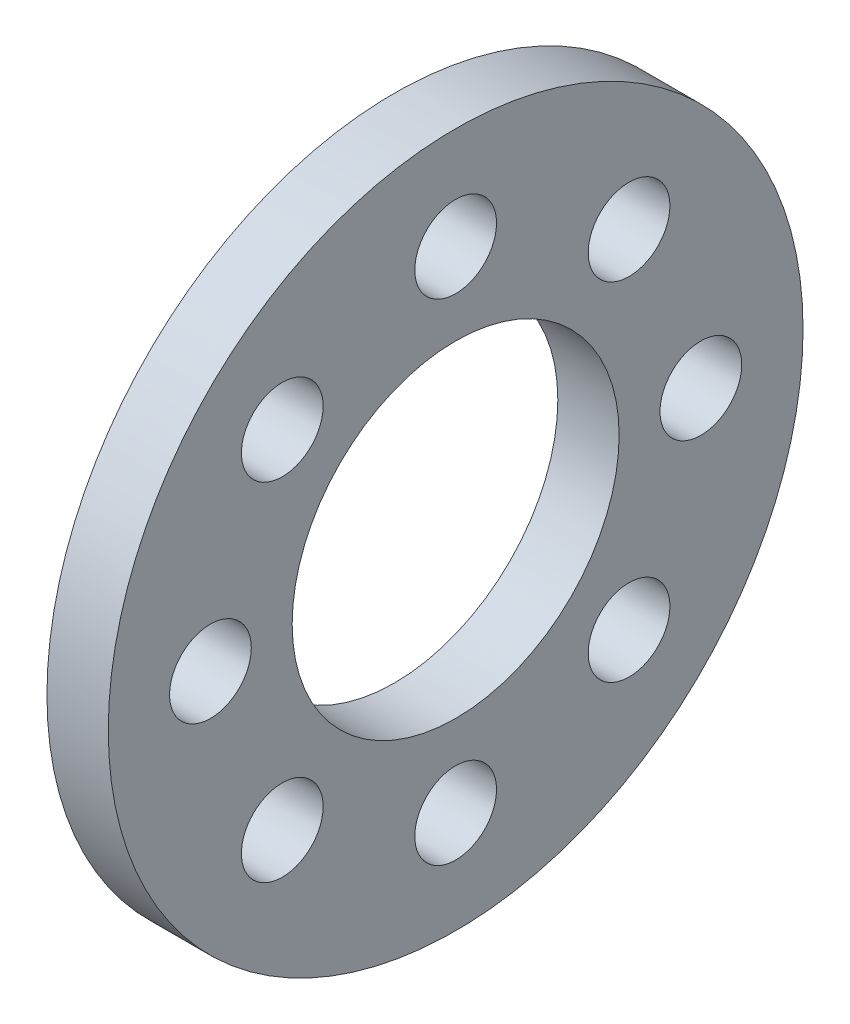
SolidWorks part; units mm, degrees
ref_plane "Front Plane" through (0, 0, 0) normal (0, 0, 1) x (1, 0, 0)
ref_plane "Top Plane" through (0, 0, 0) normal (0, 1, 0) x (1, 0, 0)
ref_plane "Right Plane" through (0, 0, 0) normal (1, 0, 0) x (0, 0, -1)
sketch "Sketch1" plane through (0, 0, 0) normal (1, 0, 0) x (0, 0, -1)
  line L0 (0, 0) -> (0, 12) construction
  circle A0 centre (0, 0) radius 17
  circle A1 centre (0, 12) radius 2
  circle A2 centre (8.4853, 8.4853) radius 2
  circle A3 centre (12, 0) radius 2
  circle A4 centre (8.4853, -8.4853) radius 2
  circle A5 centre (0, -12) radius 2
  circle A6 centre (-8.4853, -8.4853) radius 2
  circle A7 centre (-12, 0) radius 2
  circle A8 centre (-8.4853, 8.4853) radius 2
  circle A9 centre (0, 0) radius 8
  point P21 (0, 0)
  dimension "D1" = 34
  dimension "D3" = 4
  dimension "D5" = 16
  dimension "D2" = 12
  dimension "D4" = 8
extrude "Boss-Extrude1" add sketch "Sketch1" along normal blind 3
sketch "Sketch2" plane through (0, 0, 0) normal (-1, 0, 0) x (0, 0, 1)
  line L0 (0, 0) -> (-4.8186, 12.6107) construction
  line L1 (0, 0) -> (4.8186, -12.6107) construction
  circle A0 centre (-4.8186, 12.6107) radius 1.25
  circle A1 centre (4.8186, -12.6107) radius 1.25
  dimension "D3" = 2.5
  dimension "D4" = 2.5
  dimension "D1" = 13.5
  dimension "D2" = 13.5
extrude "Boss-Extrude2" add sketch "Sketch2" along normal blind 3
